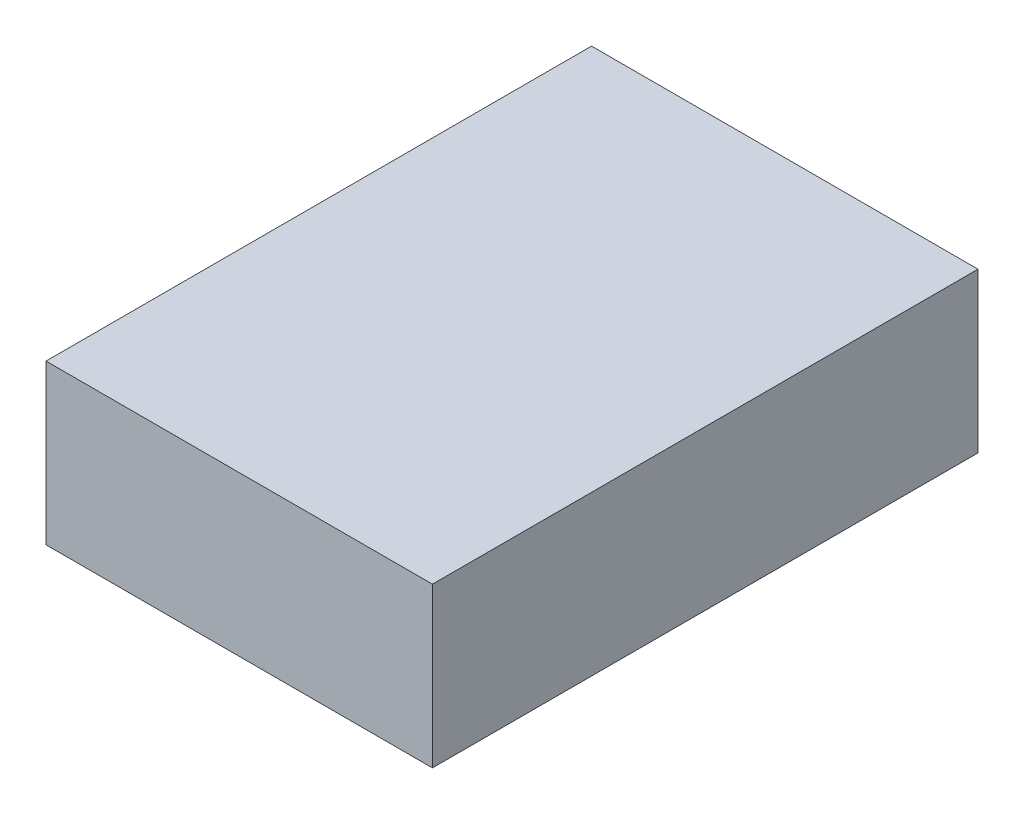
SolidWorks part; units mm, degrees
ref_plane "Front Plane" through (0, 0, 0) normal (0, 0, 1) x (1, 0, 0)
ref_plane "Top Plane" through (0, 0, 0) normal (0, 1, 0) x (1, 0, 0)
ref_plane "Right Plane" through (0, 0, 0) normal (1, 0, 0) x (0, 0, -1)
sketch "Sketch1" plane through (0, 0, 0) normal (0, 1, 0) x (1, 0, 0)
  line L1 (-17, 24) -> (17, 24)
  line L2 (-17, 24) -> (-17, -24)
  line L3 (-17, -24) -> (17, -24)
  line L4 (17, 24) -> (17, -24)
  line L5 (-17, 24) -> (17, -24) construction
  line L6 (-17, -24) -> (17, 24) construction
  point P0 (0, 0)
  dimension "D1" = 48
  dimension "D2" = 34
extrude "Boss-Extrude1" add sketch "Sketch1" along normal blind 14
